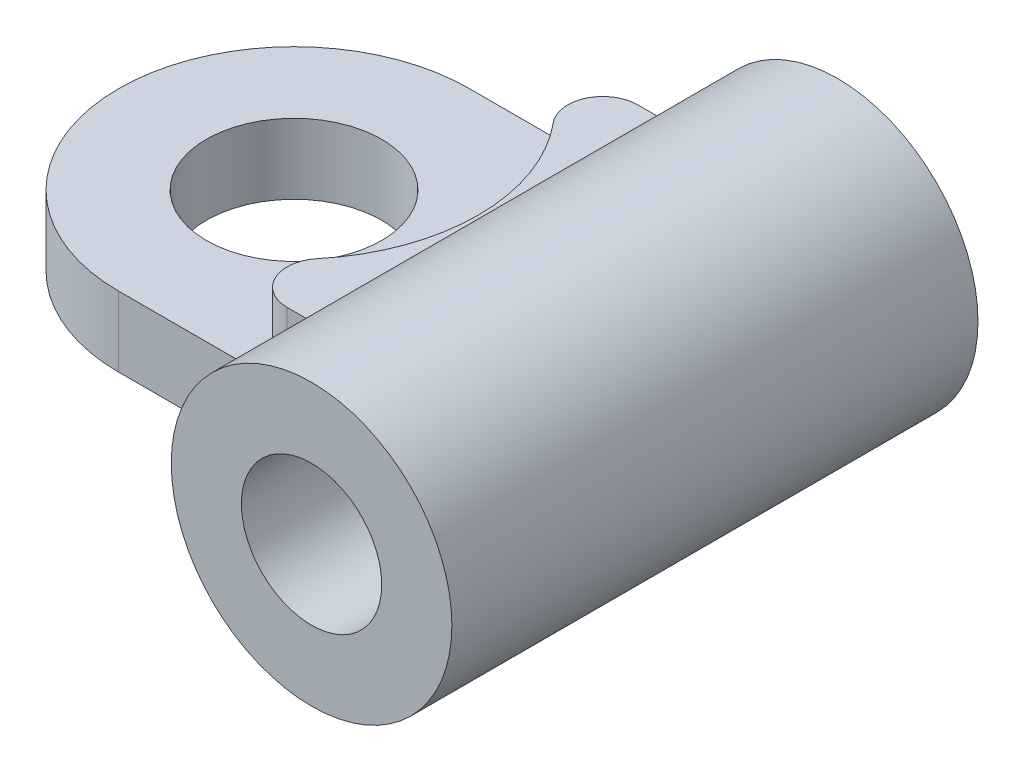
SolidWorks part; units mm, degrees
ref_plane "Спереди" through (0, 0, 0) normal (0, 0, 1) x (1, 0, 0)
ref_plane "Сверху" through (0, 0, 0) normal (0, 1, 0) x (1, 0, 0)
ref_plane "Справа" through (0, 0, 0) normal (1, 0, 0) x (0, 0, -1)
sketch "Sketch1" plane through (0, 0, 0) normal (0, 0, 1) x (1, 0, 0)
  circle A0 centre (0, 0) radius 4
  circle A1 centre (0, 0) radius 8
  dimension "D1" = 8
  dimension "D2" = 4
extrude "Boss-Extrude1" add sketch "Sketch1" along normal blind 30
sketch "Sketch2" plane through (0, 0, 0) normal (0, 1, 0) x (1, 0, 0)
  line L1 (-18, -3) -> (-5, -3)
  line L2 (-18, -23) -> (-5, -23)
  line L3 (-5, -23) -> (-5, -3)
  line L4 (8, 0) -> (-8, 0) construction
  line L5 (-8, 0) -> (-8, -30) construction
  circle A0 centre (-18, -13) radius 10
  dimension "D1" = 20
  dimension "D2" = 3
  dimension "D3" = 3
extrude "Boss-Extrude2" add sketch "Sketch2" along normal mid plane 8 separate body contours A0 | A0 L3 L1 | A0 L2 L3
sketch "Sketch3" plane through (0, 4, 0) normal (0, 1, 0) x (1, 0, 0)
  circle A0 centre (-18, -13) radius 10.5
  dimension "D1" = 21
extrude "Cut-Extrude1" cut sketch "Sketch3" against normal blind 4
fillet "Fillet1" radius 2 2 edges at (-14.7984, 2, 23) (-14.7984, 2, 3)
sketch "Sketch4" plane through (0, 0, 0) normal (0, 1, 0) x (1, 0, 0)
  circle A0 centre (-18, -13) radius 5
  dimension "D1" = 10
extrude "Cut-Extrude2" cut sketch "Sketch4" against normal blind 4
